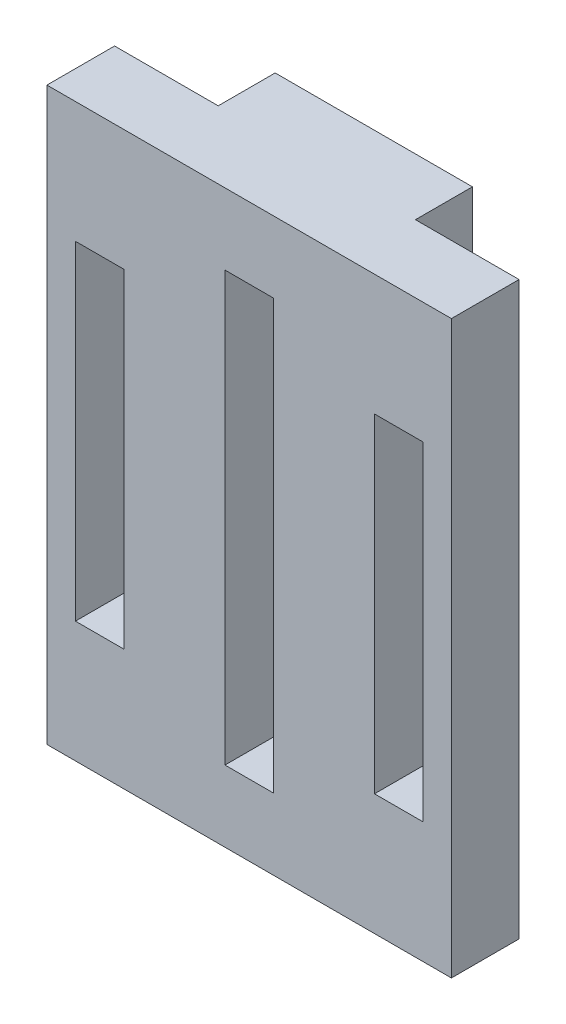
SolidWorks part; units mm, degrees
ref_plane "Front Plane" through (0, 0, 0) normal (0, 0, 1) x (1, 0, 0)
ref_plane "Top Plane" through (0, 0, 0) normal (0, 1, 0) x (1, 0, 0)
ref_plane "Right Plane" through (0, 0, 0) normal (1, 0, 0) x (0, 0, -1)
sketch "Sketch1" plane through (0, 0, 0) normal (0, 0, 1) x (1, 0, 0)
  line L1 (-14.2, 20.05) -> (14.2, 20.05)
  line L2 (-14.2, 20.05) -> (-14.2, -20.05)
  line L3 (-14.2, -20.05) -> (14.2, -20.05)
  line L4 (14.2, 20.05) -> (14.2, -20.05)
  line L5 (-14.2, 20.05) -> (14.2, -20.05) construction
  line L6 (-14.2, -20.05) -> (14.2, 20.05) construction
  point P0 (0, 0)
  dimension "D1" = 28.4
  dimension "D2" = 40.1
extrude "Boss-Extrude1" add sketch "Sketch1" along normal blind 4.75
sketch "Sketch2" plane through (0, 0, 4.75) normal (0, 0, 1) x (1, 0, 0)
  line L0 (0, -20.05) -> (0, 20.05) construction
  line L1 (14.2, 20.05) -> (-14.2, 20.05) construction
  line L2 (-10.5, 0) -> (10.5, 0) construction
  line L3 (12.2, 11.55) -> (8.8, 11.55)
  line L4 (-12.2, -11.55) -> (-8.8, -11.55)
  line L5 (-12.2, -11.55) -> (-12.2, 11.55)
  line L6 (-12.2, 11.55) -> (-8.8, 11.55)
  line L7 (-8.8, -11.55) -> (-8.8, 11.55)
  line L8 (-12.2, -11.55) -> (-8.8, 11.55) construction
  line L9 (-12.2, 11.55) -> (-8.8, -11.55) construction
  line L10 (8.8, -11.55) -> (8.8, 11.55)
  line L11 (12.2, -11.55) -> (8.8, -11.55)
  line L12 (12.2, -11.55) -> (12.2, 11.55)
  line L14 (-1.7, 15.05) -> (1.7, 15.05)
  line L15 (-1.7, 15.05) -> (-1.7, -15.05)
  line L16 (-1.7, -15.05) -> (1.7, -15.05)
  line L17 (1.7, 15.05) -> (1.7, -15.05)
  line L18 (-1.7, 15.05) -> (1.7, -15.05) construction
  line L19 (-1.7, -15.05) -> (1.7, 15.05) construction
  point P3 (0, 0)
  point P6 (0, 0)
  point P10 (0, 0)
  dimension "D1" = 21
  dimension "D2" = 3.4
  dimension "D3" = 23.1
  dimension "D4" = 3.4
  dimension "D5" = 30.1
extrude "Cut-Extrude1" cut sketch "Sketch2" against normal through all
sketch "Sketch3" plane through (0, 20.05, 0) normal (0, 1, 0) x (1, 0, 0)
  line L0 (0, 0) -> (0, -4.75) construction
  line L1 (14.2, -4.75) -> (-14.2, -4.75) construction
  circle A0 centre (0, -2.375) radius 1.0065
sketch "Sketch4" plane through (0, 0, 0) normal (0, 0, -1) x (-1, 0, 0)
  line L1 (-3.925, 15.05) -> (3.925, 15.05)
  line L2 (-3.925, 15.05) -> (-3.925, -15.05)
  line L3 (-3.925, -15.05) -> (3.925, -15.05)
  line L4 (3.925, 15.05) -> (3.925, -15.05)
  line L5 (-3.925, 15.05) -> (3.925, -15.05) construction
  line L6 (-3.925, -15.05) -> (3.925, 15.05) construction
  line L10 (-14.2, 20.05) -> (14.2, 20.05) construction
  line L11 (-6.925, 20.05) -> (6.925, 20.05)
  line L12 (-6.925, 20.05) -> (-6.925, -18.05)
  line L13 (-6.925, -18.05) -> (6.925, -18.05)
  line L14 (6.925, 20.05) -> (6.925, -18.05)
  point P0 (0, 0)
  dimension "D1" = 7.85
  dimension "D2" = 30.1
  dimension "D3" = 3
  dimension "D4" = 3
  dimension "D5" = 3
extrude "Boss-Extrude2" add sketch "Sketch4" along normal blind 4
